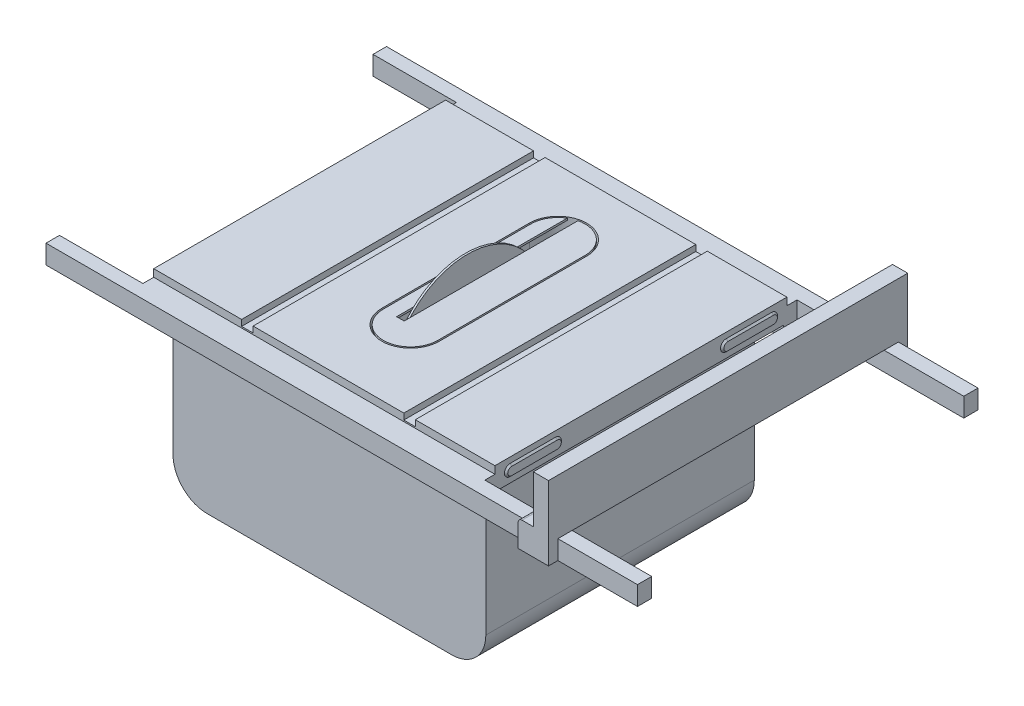
SolidWorks part; units mm, degrees
ref_plane "Front Plane" through (0, 0, 0) normal (0, 0, 1) x (1, 0, 0)
ref_plane "Top Plane" through (0, 0, 0) normal (0, 1, 0) x (1, 0, 0)
ref_plane "Right Plane" through (0, 0, 0) normal (1, 0, 0) x (0, 0, -1)
sketch "Sketch1" plane through (0, 0, 0) normal (0, 1, 0) x (1, 0, 0)
  line L0 (-285.75, -244.475) -> (285.75, 244.475) construction
  line L1 (-285.75, 244.475) -> (285.75, 244.475)
  line L2 (-285.75, 244.475) -> (-285.75, -244.475)
  line L3 (-285.75, -244.475) -> (285.75, -244.475)
  line L4 (285.75, 244.475) -> (285.75, -244.475)
  dimension "D1" = 571.5
  dimension "D2" = 488.95
extrude "Extrude1" add sketch "Sketch1" against normal blind 37.9016
sketch "Sketch2" plane through (0, -37.9016, 0) normal (0, 1, 0) x (1, 0, 0)
  line L2 (-285.75, -244.475) -> (285.75, -244.475)
  line L3 (-285.75, -244.475) -> (-285.75, -285.1547)
  line L4 (-285.75, -285.1547) -> (285.75, -285.1547)
  line L6 (285.75, -244.475) -> (285.75, -285.1547)
  line L7 (-285.75, 244.475) -> (285.75, 244.475)
  line L8 (-285.75, 244.475) -> (-285.75, 262.5328)
  line L9 (-285.75, 262.5328) -> (285.75, 262.5328)
  line L10 (285.75, 244.475) -> (285.75, 262.5328)
  dimension "D1" = 547.6875
  dimension "D2" = 40.6797
extrude "Extrude5" add sketch "Sketch2" along normal blind 25.4
sketch "Sketch6" plane through (-285.75, 0, 0) normal (-1, 0, 0) x (0, 0, 1)
  line L1 (285.1547, -12.5016) -> (261.3422, -12.5016)
  line L2 (285.1547, -12.5016) -> (285.1547, -44.2516)
  line L3 (285.1547, -44.2516) -> (261.3422, -44.2516)
  line L4 (261.3422, -12.5016) -> (261.3422, -44.2516)
  line L5 (-262.5328, -12.5016) -> (-238.7203, -12.5016)
  line L6 (-262.5328, -12.5016) -> (-262.5328, -44.2516)
  line L7 (-262.5328, -44.2516) -> (-238.7203, -44.2516)
  line L8 (-238.7203, -12.5016) -> (-238.7203, -44.2516)
  dimension "D1" = 31.75
  dimension "D2" = 23.8125
extrude "Extrude6" add sketch "Sketch6" against normal up to surface (571.5 mm away) up to face at (285.75, -17.2889, 9.3266)
sketch "Sketch7" plane through (-285.75, 0, 0) normal (-1, 0, 0) x (0, 0, 1)
  line L0 (244.475, -12.5016) -> (285.1547, -12.5016) construction
  line L1 (261.3422, -44.2516) -> (264.5172, -44.2516)
  line L2 (261.3422, -44.2516) -> (261.3422, -56.9516)
  line L3 (261.3422, -56.9516) -> (264.5172, -56.9516)
  line L4 (264.5172, -44.2516) -> (264.5172, -56.9516)
  line L5 (-238.7203, -44.2516) -> (-241.8953, -44.2516)
  line L6 (-238.7203, -44.2516) -> (-238.7203, -56.9516)
  line L7 (-238.7203, -56.9516) -> (-241.8953, -56.9516)
  line L8 (-241.8953, -44.2516) -> (-241.8953, -56.9516)
  dimension "D1" = 3.175
  dimension "D2" = 44.45
extrude "Extrude7" add sketch "Sketch7" against normal up to surface (571.5 mm away) up to face at (285.75, -26.2764, 9.988)
sketch "Sketch8" plane through (-285.75, 0, 0) normal (-1, 0, 0) x (0, 0, 1)
  line L0 (-142.875, -18.9508) -> (142.875, -18.9508) construction
  line L1 (0, 0) -> (0, -37.9016) construction
  line L2 (-238.7203, -37.9016) -> (261.3422, -37.9016) construction
  line L3 (244.475, -12.5016) -> (244.475, 0) construction
  line L4 (-219.075, -28.4758) -> (-142.875, -28.4758)
  line L5 (-219.075, -28.4758) -> (-219.075, -9.4258) construction
  line L6 (-219.075, -9.4258) -> (-142.875, -9.4258)
  line L7 (-142.875, -28.4758) -> (-142.875, -9.4258) construction
  line L8 (142.875, -28.4758) -> (219.075, -28.4758)
  line L9 (142.875, -28.4758) -> (142.875, -9.4258) construction
  line L10 (142.875, -9.4258) -> (219.075, -9.4258)
  line L11 (219.075, -28.4758) -> (219.075, -9.4258) construction
  arc A0 (-219.075, -9.4258) -> (-219.075, -28.4758) centre (-219.075, -18.9508) ccw
  arc A1 (-142.875, -9.4258) -> (-142.875, -28.4758) centre (-142.875, -18.9508) cw
  arc A2 (142.875, -9.4258) -> (142.875, -28.4758) centre (142.875, -18.9508) ccw
  arc A3 (219.075, -9.4258) -> (219.075, -28.4758) centre (219.075, -18.9508) cw
  point P7 (0, -18.9508)
  dimension "D1" = 76.2
  dimension "D2" = 25.4
  dimension "D3" = 19.05
extrude "Extrude8" add sketch "Sketch8" along normal blind 2.7781 draft 45
mirror "Mirror2" about plane through (0, 0, 0) normal (1, 0, 0) of "Extrude8"
sketch "Sketch9" plane through (56.7531, 0, -56.7531) normal (0, 1, 0) x (0, 0, -1)
  line L0 (-301.2281, 63.1031) -> (187.7219, 63.1031) construction
  line L1 (-167.4813, 94.0594) -> (79.375, 94.0594)
  line L2 (-167.4813, 94.0594) -> (-167.4813, -1.9844) construction
  line L3 (-167.4813, -1.9844) -> (79.375, -1.9844)
  line L4 (79.375, 94.0594) -> (79.375, -1.9844) construction
  line L5 (-301.2281, -228.9969) -> (187.7219, -228.9969) construction
  line L8 (-301.2281, 342.5031) -> (-301.2281, -228.9969) construction
  line L9 (187.7219, -228.9969) -> (187.7219, 342.5031) construction
  arc A0 (-167.4813, 94.0594) -> (-167.4813, -1.9844) centre (-167.4813, 46.0375) ccw
  arc A1 (79.375, 94.0594) -> (79.375, -1.9844) centre (79.375, 46.0375) cw
  dimension "D2" = 342.9
  dimension "D5" = 292.1
  dimension "D4" = 85.725
  dimension "D1" = 96.0438
  dimension "D3" = 65.0875
extrude "Extrude9" cut sketch "Sketch9" against normal through all
ref_plane "Plane3" through (565.15, 0, 0) normal (-1, 0, 0) x (0, 0, 1)
ref_plane "Plane2" through (-6.35, 0, 0) normal (1, 0, 0) x (0, 0, -1)
sketch "Sketch10" plane through (0, 0, 0) normal (0, 1, 0) x (1, 0, 0)
  line L0 (285.75, 244.475) -> (-285.75, 244.475) construction
  line L1 (-138.5094, 244.475) -> (-119.2609, 244.475)
  line L2 (-138.5094, 244.475) -> (-138.5094, -244.475)
  line L3 (-138.5094, -244.475) -> (-119.2609, -244.475)
  line L4 (-119.2609, 244.475) -> (-119.2609, -244.475)
  line L5 (285.75, -244.475) -> (-285.75, -244.475) construction
  line L6 (-285.75, -244.475) -> (285.75, -244.475) construction
  line L7 (133.1516, 244.475) -> (152.4, 244.475)
  line L8 (133.1516, 244.475) -> (133.1516, -244.475)
  line L9 (133.1516, -244.475) -> (152.4, -244.475)
  line L10 (152.4, 244.475) -> (152.4, -244.475)
  line L11 (285.75, -244.475) -> (285.75, 244.475) construction
  dimension "D1" = 19.2484
  dimension "D2" = 252.4125
  dimension "D3" = 133.35
extrude "Extrude10" cut sketch "Sketch10" against normal blind 10.1203
sketch "Sketch3" plane through (0, 0, 0) normal (1, 0, 0) x (0, 0, -1)
  line L0 (-261.3422, -37.9016) -> (-261.3422, -56.9516) construction
  line L1 (-285.1547, -12.5016) -> (-261.3422, -12.5016)
  line L2 (-285.1547, -12.5016) -> (-285.1547, -44.2516)
  line L3 (-285.1547, -44.2516) -> (-261.3422, -44.2516)
  line L4 (-261.3422, -12.5016) -> (-261.3422, -44.2516)
  line L5 (-264.5172, -44.2516) -> (-285.1547, -44.2516) construction
extrude "Extrude3" add sketch "Sketch3" along normal up to surface (565.15 mm away) up to plane "Plane3"
mirror "Mirror1" about plane through (0, 0, 0) normal (0, 0, 1) of "Extrude3"
sketch "Sketch4" plane through (0, 0, 285.1547) normal (0, 0, 1) x (1, 0, 0)
  line L0 (381, 0) -> (406.4, 0)
  line L1 (406.4, 0) -> (406.4, 79.5734)
  line L2 (406.4, 79.5734) -> (431.8, 79.5734)
  line L3 (431.8, 79.5734) -> (431.8, -12.5016)
  line L4 (-285.75, -12.5016) -> (565.15, -12.5016) construction
  line L5 (431.8, -12.5016) -> (381, -12.5016)
  line L6 (381, -12.5016) -> (381, 0)
  line L9 (152.4, 0) -> (285.75, 0) construction
  line L11 (285.75, -12.5016) -> (285.75, 0) construction
  dimension "D1" = 25.4
  dimension "D2" = 25.4
  dimension "D3" = 120.65
  dimension "D4" = 92.075
extrude "Extrude4" add sketch "Sketch4" against normal up to surface (570.3094 mm away) up to face at (282.575, -28.3766, -285.1547)
sketch "Sketch11" plane through (0, 0, 285.1547) normal (0, 0, 1) x (1, 0, 0)
  line L0 (565.15, -44.2516) -> (-285.75, -44.2516) construction
  line L1 (431.8, 79.5734) -> (406.4, 79.5734)
  line L2 (431.8, 79.5734) -> (431.8, -44.2516)
  line L3 (431.8, -44.2516) -> (406.4, -44.2516)
  line L4 (406.4, 79.5734) -> (406.4, -44.2516)
  line L5 (406.4, 79.5734) -> (406.4, 0) construction
extrude "Extrude11" add sketch "Sketch11" along normal blind 15.6766
mirror "Mirror3" about plane through (0, 0, 0) normal (0, 0, 1) of "Extrude11"
sketch "Sketch12" plane through (0, 0, 285.1547) normal (0, 0, 1) x (1, 0, 0)
  line L1 (381, 0) -> (406.4, 0)
  line L2 (381, 0) -> (381, -44.2516)
  line L3 (381, -44.2516) -> (406.4, -44.2516)
  line L4 (406.4, 0) -> (406.4, -44.2516)
extrude "Extrude12" add sketch "Sketch12" along normal up to surface (15.6766 mm away) up to face at (419.1, 17.6609, 300.8313)
sketch "Sketch13" plane through (0, 0, -300.8313) normal (0, 0, -1) x (-1, 0, 0)
  line L4 (-381, 0) -> (-406.4, 0)
  line L5 (-406.4, 0) -> (-406.4, -44.2516)
  line L6 (-406.4, -44.2516) -> (-381, -44.2516)
  line L7 (-381, -44.2516) -> (-381, 0)
  line L8 (-381, 0) -> (-406.4, 0)
  line L9 (-406.4, 0) -> (-406.4, -44.2516)
  line L10 (-406.4, -44.2516) -> (-381, -44.2516)
  line L11 (-381, -44.2516) -> (-381, 0)
  dimension "D1" = 0
extrude "Extrude13" add sketch "Sketch13" against normal up to surface (15.6766 mm away) up to face at (298.45, -15.2301, -285.1547)
fillet "Fillet1" radius 6.35 1 edges at (381, 0, 0)
ref_plane "Plane1" through (0, 0, 224.8297) normal (0, 0, 1) x (1, 0, 0)
sketch "Sketch14" plane through (0, 0, 224.8297) normal (0, 0, 1) x (1, 0, 0)
  line L0 (-285.75, -37.9016) -> (285.75, -37.9016) construction
  line L1 (-273.05, -37.9016) -> (250.825, -37.9016)
  line L2 (-273.05, -37.9016) -> (-273.05, -273.05)
  line L3 (-215.9, -330.2) -> (193.675, -330.2)
  line L4 (250.825, -37.9016) -> (250.825, -273.05)
  line L5 (-285.75, -12.5016) -> (-285.75, -44.2516) construction
  line L6 (285.75, -56.9516) -> (285.75, -44.2516) construction
  line L7 (-119.2609, 0) -> (133.1516, 0) construction
  arc A0 (-273.05, -273.05) -> (-215.9, -330.2) centre (-215.9, -273.05) ccw
  arc A1 (250.825, -273.05) -> (193.675, -330.2) centre (193.675, -273.05) cw
  dimension "D1" = 57.15
  dimension "D2" = 12.7
  dimension "D3" = 34.925
  dimension "D4" = 330.2
extrude "Extrude14" add sketch "Sketch14" against normal up to surface (224.8297 mm away) up to plane "Front Plane"
mirror "Mirror6" about plane through (0, 0, 0) normal (0, 0, 1) of "Extrude14"
sketch "Sketch15" plane through (-6.35, 0, 0) normal (1, 0, 0) x (0, 0, -1)
  line L0 (0, -87.8201) -> (0, 0) construction
  line L1 (-244.475, 0) -> (244.475, 0) construction
  circle A0 centre (0, -87.8201) radius 127
  dimension "D1" = 254
extrude "Extrude15" add sketch "Sketch15" along normal mid plane 3.175
sketch "Sketch16" plane through (0, 0, 0) normal (0, 1, 0) x (1, 0, 0)
  line L0 (-37.3063, 136.1281) -> (-37.3062, -110.7281) construction
  line L1 (58.7375, -110.7281) -> (58.7375, 136.1281) construction
  line L2 (-37.3063, 136.1281) -> (-37.3062, -110.7281) construction
  line L3 (58.7375, -110.7281) -> (58.7375, 136.1281) construction
  line L4 (-34.7662, 136.1281) -> (-34.7662, -110.7281)
  line L5 (56.1975, -110.7281) -> (56.1975, 136.1281)
  line L6 (-12.7, 175.1193) -> (-12.7, -110.7281)
  line L7 (-12.7, -110.7281) -> (0, -110.7281)
  line L8 (0, -110.7281) -> (0, 180.3297)
  line L9 (-6.35, -110.7281) -> (-6.35, 136.1281) construction
  line L10 (-6.35, -244.475) -> (-6.35, 244.475) construction
  line L11 (-37.3063, 136.1281) -> (58.7375, 136.1281) construction
  arc A0 (-37.3062, -110.7281) -> (58.7375, -110.7281) centre (10.7156, -110.7281) ccw construction
  arc A1 (58.7375, 136.1281) -> (-37.3063, 136.1281) centre (10.7156, 136.1281) ccw construction
  arc A2 (-37.3062, -110.7281) -> (58.7375, -110.7281) centre (10.7156, -110.7281) ccw construction
  arc A3 (58.7375, 136.1281) -> (-37.3063, 136.1281) centre (10.7156, 136.1281) ccw construction
  arc A4 (-34.7662, -110.7281) -> (56.1975, -110.7281) centre (10.7156, -110.7281) ccw
  arc A5 (56.1975, 136.1281) -> (0, 180.3297) centre (10.7156, 136.1281) ccw
  arc A6 (-12.7, 175.1193) -> (-34.7662, 136.1281) centre (10.7156, 136.1281) ccw
  arc A7 (56.1975, 136.1281) -> (-34.7662, 136.1281) centre (10.7156, 136.1281) ccw construction
  dimension "D2" = 12.7
  dimension "D1" = 2.54
extrude "Extrude16" add sketch "Sketch16" against normal blind 3.175
sketch "Sketch17" plane through (0, 0, -224.8297) normal (0, 0, -1) x (-1, 0, 0)
  line L0 (215.9, -330.2) -> (-193.675, -330.2) construction
  line L1 (-250.825, -273.05) -> (-250.825, -37.9016) construction
  line L2 (6.35, 39.1799) -> (6.35, -254) construction
  line L3 (7.9375, 39.1799) -> (4.7625, 39.1799) construction
  circle A0 centre (6.35, -254) radius 29.21
  circle A1 centre (6.35, -254) radius 31.75
  dimension "D2" = 63.5
  dimension "D4" = 257.175
  dimension "D3" = 76.2
  dimension "D1" = 2.54
extrude "Extrude17" add sketch "Sketch17" along normal blind 12.7
sketch "Sketch18" plane through (0, 0, -224.8297) normal (0, 0, -1) x (-1, 0, 0)
  line L0 (215.9, -330.2) -> (-193.675, -330.2) construction
  line L1 (-95.25, -152.4) -> (107.95, -152.4)
  line L2 (-95.25, -152.4) -> (-95.25, -298.45)
  line L3 (-95.25, -298.45) -> (107.95, -298.45)
  line L4 (107.95, -152.4) -> (107.95, -298.45)
  circle A0 centre (6.35, -254) radius 29.21 construction
  circle A1 centre (6.35, -254) radius 31.75 construction
  circle A2 centre (6.35, -254) radius 29.21
  circle A3 centre (6.35, -254) radius 31.75
  circle M7 centre (6.35, -254) radius 31.75
  dimension "D1" = 31.75
  dimension "D2" = 101.6
  dimension "D3" = 101.6
  dimension "D4" = 101.6
extrude "Extrude18" cut sketch "Sketch18" against normal blind 76.2 contours L4 L1 L2 L3 M7 | A2
sketch "Sketch19" plane through (0, 0, 0) normal (0, 1, 0) x (1, 0, 0)
  line L0 (419.1, 280.1937) -> (419.1, -300.8313) construction
  line L1 (431.8, -300.8313) -> (406.4, -300.8313) construction
  dimension "D1" = 581.025
ref_plane "Plane4" through (-425.45, 0, 0) normal (-1, 0, 0) x (0, 0, 1)
sketch "Sketch20" plane through (-285.75, 0, 0) normal (-1, 0, 0) x (0, 0, 1)
  line L1 (-262.5328, -44.2516) -> (-285.1547, -44.2516)
  line L2 (-262.5328, -44.2516) -> (-262.5328, -12.5016)
  line L3 (-262.5328, -12.5016) -> (-285.1547, -12.5016)
  line L4 (-285.1547, -44.2516) -> (-285.1547, -12.5016)
  line L6 (285.1547, -12.5016) -> (262.5328, -12.5016)
  line L7 (285.1547, -12.5016) -> (285.1547, -44.2516)
  line L8 (285.1547, -44.2516) -> (262.5328, -44.2516)
  line L9 (262.5328, -12.5016) -> (262.5328, -44.2516)
extrude "Extrude20" add sketch "Sketch20" against normal up to surface and the other way up to surface
